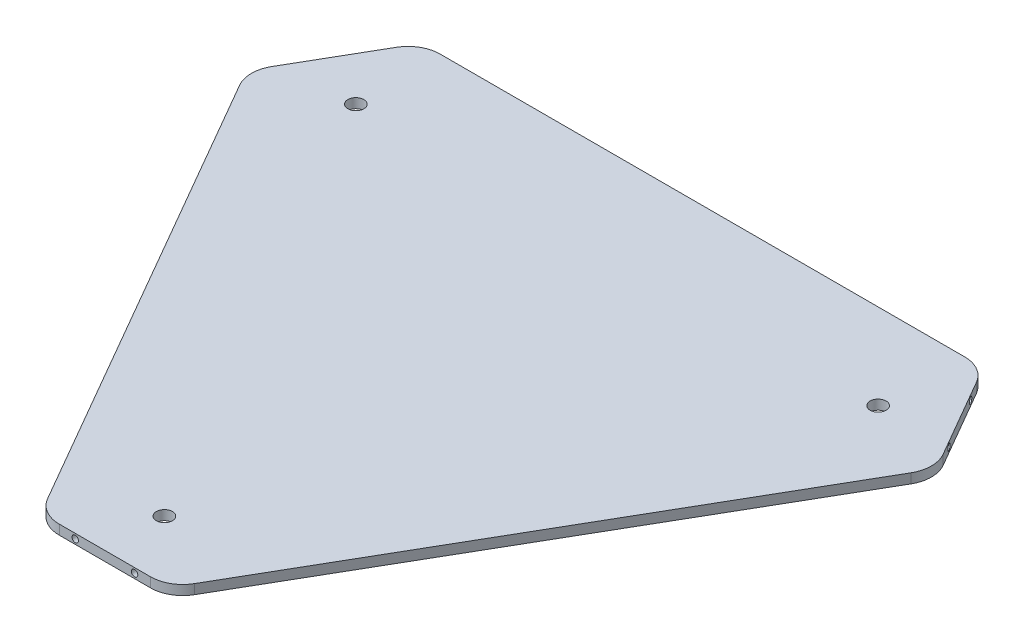
SolidWorks part; units mm, degrees
ref_plane "Front Plane" through (0, 0, 0) normal (0, 0, 1) x (1, 0, 0)
ref_plane "Top Plane" through (0, 0, 0) normal (0, 1, 0) x (1, 0, 0)
ref_plane "Right Plane" through (0, 0, 0) normal (1, 0, 0) x (0, 0, -1)
sketch "Sketch1" plane through (0, 0, 0) normal (0, 1, 0) x (1, 0, 0)
  line L0 (-132.8622, 80.6266) -> (-114.8184, 111.8764)
  line L1 (114.7578, 111.8982) -> (132.8579, 80.6002)
  line L2 (-103.821, 118.2259) -> (103.763, 118.2403)
  line L3 (-18.0944, -118.2403) -> (18.0401, -118.2403)
  line L4 (-132.8638, 67.9283) -> (-29.0942, -111.8881)
  line L5 (132.8618, 67.891) -> (29.038, -111.8915)
  line L6 (-84.0133, 67.0223) -> (-78.6427, 76.3234)
  line L7 (84.1416, 67.0751) -> (78.7703, 76.363)
  line L8 (-84.0158, 54.3257) -> (-16.3805, -62.9162)
  line L9 (-5.3798, -69.27) -> (5.3567, -69.27)
  line L10 (16.3521, -62.9253) -> (84.1432, 54.3618)
  line L11 (67.7734, 82.705) -> (-67.6475, 82.673)
  arc A0 (18.0401, -118.2403) -> (29.038, -111.8915) centre (18.0401, -105.5403) ccw
  arc A1 (-29.0942, -111.8881) -> (-18.0944, -118.2403) centre (-18.0944, -105.5403) ccw
  arc A2 (132.8618, 67.891) -> (132.8579, 80.6002) centre (121.864, 74.2422) ccw
  arc A3 (114.7578, 111.8982) -> (103.763, 118.2403) centre (103.7639, 105.5403) ccw
  arc A4 (-103.821, 118.2259) -> (-114.8184, 111.8764) centre (-103.8201, 105.5259) ccw
  arc A5 (-132.8622, 80.6266) -> (-132.8638, 67.9283) centre (-121.864, 74.2761) ccw
  arc A6 (-16.3805, -62.9162) -> (-5.3798, -69.27) centre (-5.3798, -56.57) ccw
  arc A7 (5.3567, -69.27) -> (16.3521, -62.9253) centre (5.3567, -56.57) ccw
  arc A8 (84.1432, 54.3618) -> (84.1416, 67.0751) centre (73.1477, 60.7171) ccw
  arc A9 (78.7703, 76.363) -> (67.7734, 82.705) centre (67.7764, 70.005) ccw
  arc A10 (-67.6475, 82.673) -> (-78.6427, 76.3234) centre (-67.6445, 69.973) ccw
  arc A11 (-84.0133, 67.0223) -> (-84.0158, 54.3257) centre (-73.015, 60.6719) ccw
  circle A12 centre (-103.3309, 84.381) radius 3.175
  circle A13 centre (-0.0284, -94.7026) radius 3.175
  circle A14 centre (103.3369, 84.3971) radius 3.175
  dimension "D1" = 6.35
  dimension "D2" = 12.7
  dimension "D4" = 5.3567
  dimension "D5" = 16.3521
  dimension "D6" = 18.0401
  dimension "D7" = 29.038
  dimension "D8" = 67.7734
  dimension "D9" = 67.7764
  dimension "D10" = 73.1477
  dimension "D11" = 78.7703
  dimension "D12" = 103.763
  dimension "D13" = 103.3369
  dimension "D14" = 103.7639
  dimension "D15" = 114.7578
  dimension "D16" = 121.864
  dimension "D17" = 5.3798
  dimension "D18" = 16.3805
  dimension "D19" = 18.0944
  dimension "D20" = 0.0284
  dimension "D21" = 29.0942
  dimension "D22" = 67.6445
  dimension "D23" = 73.015
  dimension "D24" = 103.8201
  dimension "D25" = 114.8184
  dimension "D26" = 54.3257
  dimension "D27" = 67.891
  dimension "D31" = 103.3309
  dimension "D45" = 84.381
  dimension "D46" = 84.3971
  dimension "D57" = 94.7026
extrude "Boss-Extrude1" add sketch "Sketch1" along normal blind 3.81
sketch "Sketch2" plane through (0, 0, 0) normal (0, 1, 0) x (1, 0, 0)
  line L0 (-80.979, -21.9799) -> (123.8078, 96.2492) construction
  line L1 (-132.8638, 67.9283) -> (-29.0942, -111.8881) construction
  line L2 (114.7578, 111.8982) -> (132.8579, 80.6002) construction
  line L3 (-0.029, 118.2331) -> (-0.0271, -118.2403) construction
  line L4 (-103.821, 118.2259) -> (103.763, 118.2403) construction
  line L5 (-18.0944, -118.2403) -> (18.0401, -118.2403) construction
  line L6 (80.9499, -22.0002) -> (-123.8403, 96.2515) construction
  line L7 (132.8618, 67.891) -> (29.038, -111.8915) construction
  line L8 (-132.8622, 80.6266) -> (-114.8184, 111.8764) construction
  line L9 (-129.7133, 86.0802) -> (-136.3122, 89.8906) construction
  line L10 (-117.967, 106.4226) -> (-124.5659, 110.233) construction
  line L11 (-117.967, 106.4226) -> (-0.0283, 24.7552) construction
  line L12 (-0.0283, 24.7552) -> (-129.7133, 86.0802) construction
  line L13 (-129.7133, 86.0802) -> (-85.715, 60.6744) construction
  line L14 (129.6671, 86.0594) -> (136.2665, 89.8691) construction
  line L15 (117.9233, 106.4032) -> (124.5226, 110.2128) construction
  line L16 (129.6671, 86.0594) -> (-0.0283, 24.7552) construction
  line L17 (-0.0283, 24.7552) -> (117.9233, 106.4032) construction
  line L18 (-11.7849, -118.2164) -> (-11.7854, -125.8364) construction
  line L19 (11.7052, -118.2178) -> (11.7048, -125.8378) construction
  line L20 (-11.7849, -118.2164) -> (-0.0283, 24.7552) construction
  line L21 (-0.0283, 24.7552) -> (11.7052, -118.2178) construction
  line L22 (-108.0075, 24.7552) -> (107.951, 24.7552) construction
  line L23 (29.038, -111.8915) -> (132.8618, 67.891) construction
  arc A0 (-84.0133, 67.0223) -> (-84.0158, 54.3257) centre (-73.015, 60.6719) ccw construction
  point P18 (-0.0283, 24.7552)
  point P27 (-0.0283, 24.7552)
  dimension "D1" = 7.62
  dimension "D2" = 3
sketch "Sketch3" plane through (134.4902, 0, -77.7777) normal (0.8657, 0, -0.5006) x (-0.5006, 0, -0.8657)
  line L0 (9.5837, 1.905) -> (33.0739, 1.905) construction
  line L1 (9.5837, 1.905) -> (9.5837, 0) construction
  line L2 (9.5837, 0) -> (9.5778, 0) construction
  line L3 (33.0739, 1.905) -> (33.0739, 0) construction
  line L5 (3.2605, 0) -> (39.4154, 0) construction
  line L6 (21.3379, 3.81) -> (21.3379, 0) construction
  line L7 (3.2605, 3.81) -> (39.4154, 3.81) construction
  circle A0 centre (9.5837, 1.905) radius 1.27
  circle A1 centre (33.0739, 1.905) radius 1.27
  point P4 (21.3379, 1.905)
  dimension "D1" = 2.54
extrude "Cut-Extrude1" cut sketch "Sketch3" against normal up to next
sketch "Sketch5" plane through (0, 0, 118.2403) normal (0, 0, 1) x (1, 0, 0)
  line L0 (-11.7849, 1.905) -> (11.7052, 1.905) construction
  line L1 (-11.7849, 1.905) -> (-11.7849, 0) construction
  line L2 (11.7052, 1.905) -> (11.7052, 0) construction
  line L3 (-0.0271, 3.81) -> (-0.0271, 0) construction
  line L4 (11.7052, 0) -> (11.7048, 0) construction
  line L5 (-0.029, 0) -> (-0.0271, 0) construction
  line L6 (-18.0944, 0) -> (18.0401, 0) construction
  line L7 (-18.0944, 3.81) -> (18.0401, 3.81) construction
  circle A0 centre (-11.7849, 1.905) radius 1.27
  circle A1 centre (11.7052, 1.905) radius 1.27
  point P4 (-0.0271, 1.905)
  point P9 (0, 0)
  point P11 (0, 0)
  point P14 (0, 0)
  point P17 (10.4465, 0)
  point P21 (-11.7849, 2.1883)
  point P22 (0, 0)
  point P25 (2.7242, 3.81)
  point P26 (0, 0)
  point P27 (0, 0)
  dimension "D1" = 2.54
extrude "Cut-Extrude2" cut sketch "Sketch5" against normal up to next
sketch "Sketch6" plane through (-134.5558, 0, -77.6936) normal (-0.866, 0, -0.5) x (-0.5, 0, 0.866)
  line L0 (-33.1744, 1.905) -> (-9.6843, 1.905) construction
  line L1 (-33.1744, 1.905) -> (-33.1744, 0) construction
  line L2 (-9.6843, 1.905) -> (-9.6843, 0) construction
  line L3 (-21.4294, 3.81) -> (-21.4294, 0) construction
  line L4 (-39.4719, 3.81) -> (-3.3868, 3.81) construction
  line L5 (-39.4719, 0) -> (-3.3868, 0) construction
  circle A0 centre (-33.1744, 1.905) radius 1.27
  circle A1 centre (-9.6843, 1.905) radius 1.27
  point P4 (-21.4294, 1.905)
  point P11 (0, 0)
  point P14 (-35.2064, 0)
  dimension "D1" = 2.54
extrude "Cut-Extrude3" cut sketch "Sketch6" against normal up to next
sketch "Sketch7" plane through (0, 0, 0) normal (0, 1, 0) x (1, 0, 0)
  line L0 (84.1416, 67.0751) -> (78.7703, 76.363) construction
  line L1 (16.3521, -62.9253) -> (84.1432, 54.3618) construction
  line L2 (-5.3798, -69.27) -> (5.3567, -69.27) construction
  line L3 (-84.0158, 54.3257) -> (-16.3805, -62.9162) construction
  line L4 (-78.6427, 76.3234) -> (-84.0133, 67.0223) construction
  line L5 (67.7734, 82.705) -> (-67.6475, 82.673) construction
  line L6 (84.1416, 67.0751) -> (78.7703, 76.363)
  line L7 (16.3521, -62.9253) -> (84.1432, 54.3618)
  line L8 (-5.3798, -69.27) -> (5.3567, -69.27)
  line L9 (-84.0158, 54.3257) -> (-16.3805, -62.9162)
  line L10 (-78.6427, 76.3234) -> (-84.0133, 67.0223)
  line L11 (67.7734, 82.705) -> (-67.6475, 82.673)
  arc A0 (78.7703, 76.363) -> (67.7734, 82.705) centre (67.7764, 70.005) ccw construction
  arc A1 (84.1432, 54.3618) -> (84.1416, 67.0751) centre (73.1477, 60.7171) ccw construction
  arc A2 (5.3567, -69.27) -> (16.3521, -62.9253) centre (5.3567, -56.57) ccw construction
  arc A3 (-16.3805, -62.9162) -> (-5.3798, -69.27) centre (-5.3798, -56.57) ccw construction
  arc A4 (-84.0133, 67.0223) -> (-84.0158, 54.3257) centre (-73.015, 60.6719) ccw construction
  arc A5 (-67.6475, 82.673) -> (-78.6427, 76.3234) centre (-67.6445, 69.973) ccw construction
  arc A6 (78.7703, 76.363) -> (67.7734, 82.705) centre (67.7764, 70.005) ccw
  arc A7 (84.1432, 54.3618) -> (84.1416, 67.0751) centre (73.1477, 60.7171) ccw
  arc A8 (5.3567, -69.27) -> (16.3521, -62.9253) centre (5.3567, -56.57) ccw
  arc A9 (-16.3805, -62.9162) -> (-5.3798, -69.27) centre (-5.3798, -56.57) ccw
  arc A10 (-84.0133, 67.0223) -> (-84.0158, 54.3257) centre (-73.015, 60.6719) ccw
  arc A11 (-67.6475, 82.673) -> (-78.6427, 76.3234) centre (-67.6445, 69.973) ccw
extrude "Boss-Extrude2" add sketch "Sketch7" along normal up to surface (3.81 mm away) up to face at (-0.0284, 3.81, 97.8776)
